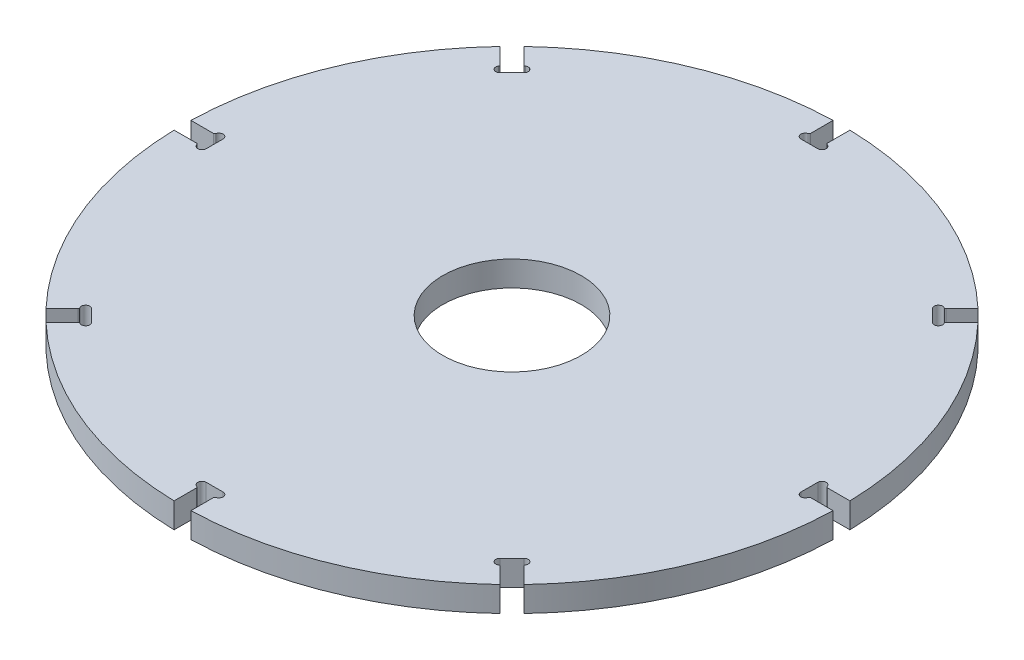
SolidWorks part; units mm, degrees
ref_plane "Front Plane" through (0, 0, 0) normal (0, 0, 1) x (1, 0, 0)
ref_plane "Top Plane" through (0, 0, 0) normal (0, 1, 0) x (1, 0, 0)
ref_plane "Right Plane" through (0, 0, 0) normal (1, 0, 0) x (0, 0, -1)
sketch "Sketch1" plane through (0, 0, 0) normal (0, 1, 0) x (1, 0, 0)
  circle A0 centre (0, 0) radius 52.5
  circle A1 centre (0, 0) radius 250
  dimension "D1" = 105
  dimension "D2" = 500
extrude "Boss-Extrude1" add sketch "Sketch1" along normal blind 19.05
sketch "Sketch2" plane through (0, 19.05, 0) normal (0, 1, 0) x (1, 0, 0)
  line L0 (0, 0) -> (0, 52.5) construction
  line L1 (0, 52.5) -> (0, 250) construction
  line L2 (0, 52.5) -> (0, 225.5) construction
  line L3 (0, 225.5) -> (0, 250) construction
  line L4 (6.4, 225.5) -> (6.4, 250) construction
  line L5 (-6.4, 225.5) -> (-6.4, 250) construction
  line L6 (6.4, 225.5) -> (-6.4, 225.5)
  line L7 (6.4, 250) -> (-6.4, 250)
  line L8 (-6.4, 250) -> (-6.4, 231.9)
  line L9 (6.4, 250) -> (6.4, 231.9)
  circle A0 centre (0, 0) radius 52.5 construction
  circle A1 centre (0, 0) radius 250 construction
  arc A2 (-6.4, 231.9) -> (-6.4, 225.5) centre (-6.4, 228.7) ccw
  arc A3 (6.4, 225.5) -> (6.4, 231.9) centre (6.4, 228.7) ccw
  dimension "D4" = 6.4
  dimension "D1" = 225.5
  dimension "D2" = 6.4
  dimension "D3" = 6.4
extrude "Cut-Extrude1" cut sketch "Sketch2" against normal through all
fillet "Fillet1" radius 1 2 edges at (6.4, 9.525, -231.9) (-6.4, 9.525, -231.9)
pattern_circular "CirPattern1" count 8 over 360 about axis through (0, 0, 0) along (0, 1, 0) of "Fillet1", "Cut-Extrude1"
